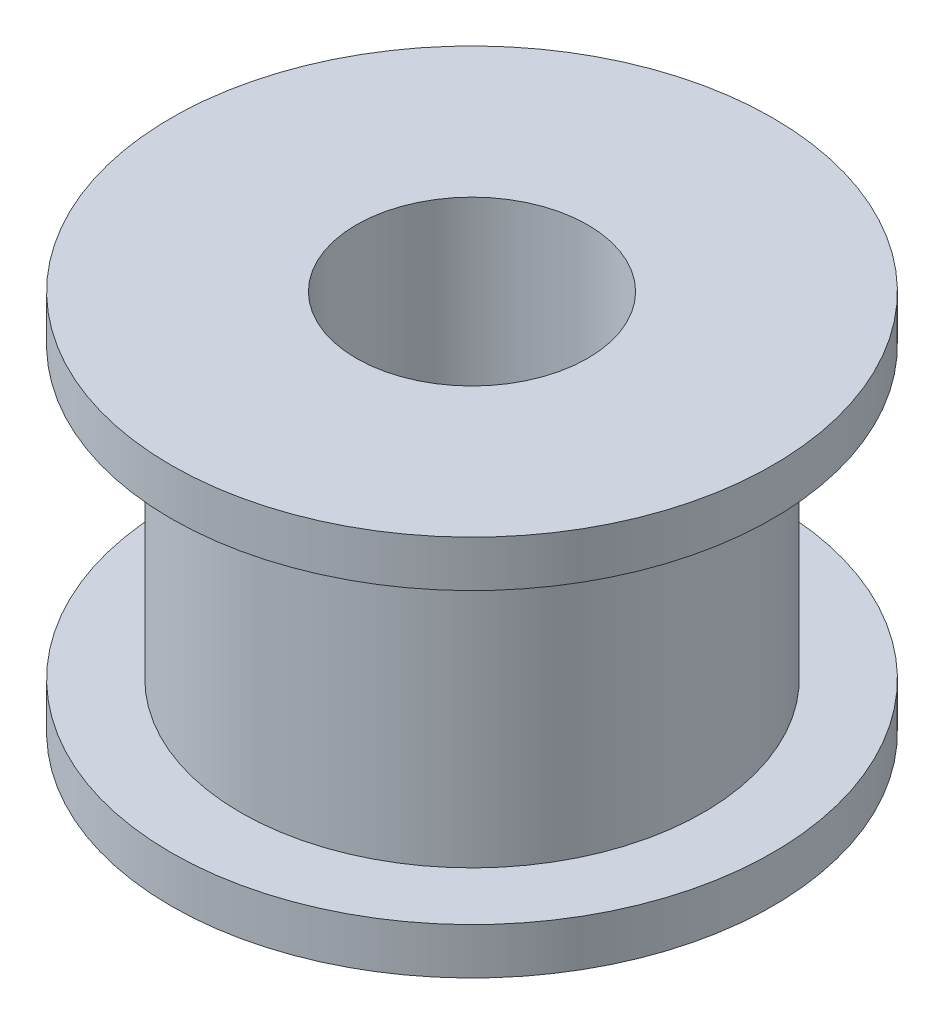
SolidWorks part; units mm, degrees
ref_plane "Plan de face" through (0, 0, 0) normal (0, 0, 1) x (1, 0, 0)
ref_plane "Plan de dessus" through (0, 0, 0) normal (0, 1, 0) x (1, 0, 0)
ref_plane "Plan de droite" through (0, 0, 0) normal (1, 0, 0) x (0, 0, -1)
sketch "Esquisse1" plane through (0, 0, 0) normal (0, 0, 1) x (1, 0, 0)
  line L3 (-2.5, -8.25) -> (-2.5, 0)
  line L6 (-6.5, 0) -> (-6.5, -1)
  line L7 (-6.5, -1) -> (-5, -1)
  line L8 (-5, -1) -> (-5, -7.25)
  line L9 (-5, -7.25) -> (-6.5, -7.25)
  line L10 (-6.5, -7.25) -> (-6.5, -8.25)
  line L11 (-6.5, -8.25) -> (-2.5, -8.25)
  line L12 (-2.5, 0) -> (-6.5, 0)
  line L13 (0, 0) -> (0, -1.4765) construction
  dimension "D1" = 2.5
  dimension "D2" = 1.5
  dimension "D3" = 1
  dimension "D4" = 6.25
  dimension "D5" = 2.5
revolve "Révolution1" add sketch "Esquisse1" angle 360 about L13
